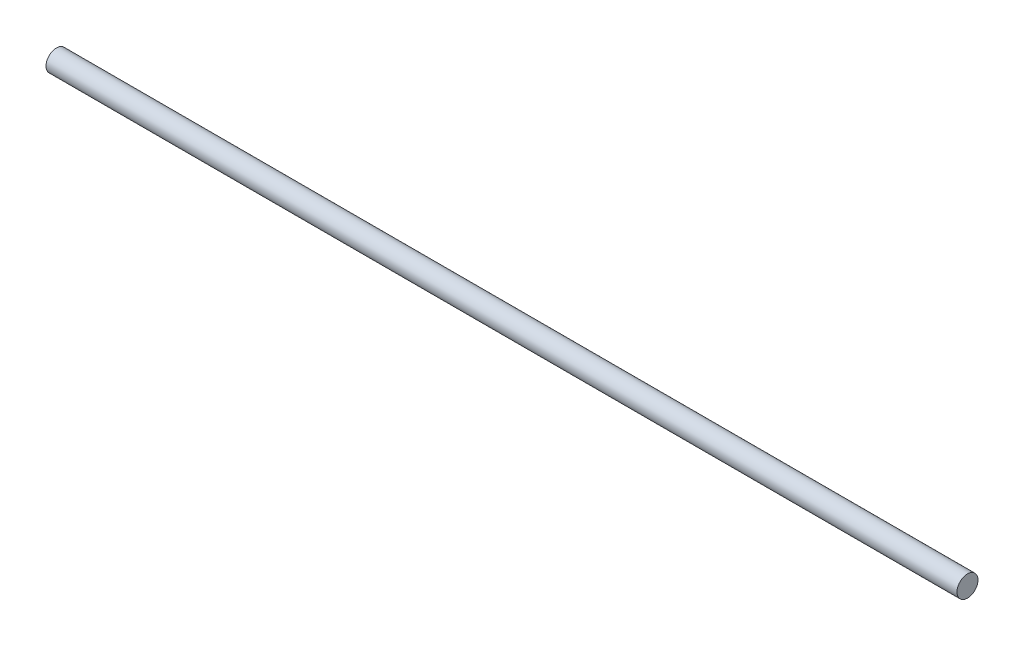
SolidWorks part; units mm, degrees
ref_plane "Front Plane" through (0, 0, 0) normal (0, 0, 1) x (1, 0, 0)
ref_plane "Top Plane" through (0, 0, 0) normal (0, 1, 0) x (1, 0, 0)
ref_plane "Right Plane" through (0, 0, 0) normal (1, 0, 0) x (0, 0, -1)
sketch "Sketch1" plane through (0, 0, 0) normal (1, 0, 0) x (0, 0, -1)
  circle A0 centre (0, 0) radius 3
extrude "Boss-Extrude1" add sketch "Sketch1" along normal mid plane 260
